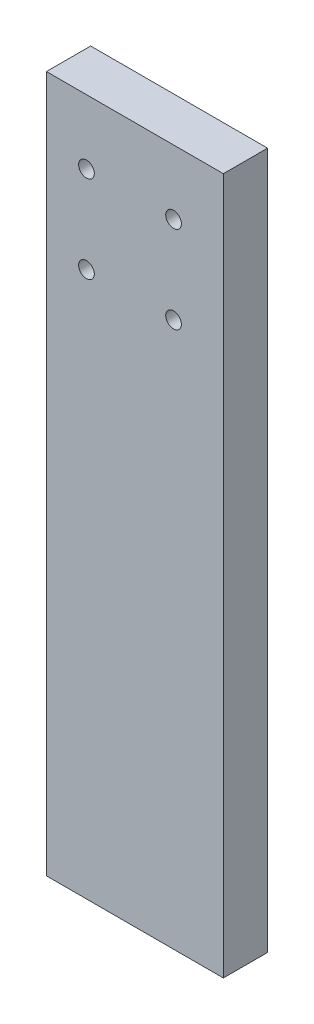
SolidWorks part; units mm, degrees
ref_plane "Alzado" through (0, 0, 0) normal (0, 0, 1) x (1, 0, 0)
ref_plane "Planta" through (0, 0, 0) normal (0, 1, 0) x (1, 0, 0)
ref_plane "Vista lateral" through (0, 0, 0) normal (1, 0, 0) x (0, 0, -1)
sketch "Croquis1" plane through (0, 0, 0) normal (0, 0, 1) x (1, 0, 0)
  line L1 (-24, 62) -> (26.8, 62)
  line L2 (-24, 62) -> (-24, -138)
  line L3 (-24, -138) -> (26.8, -138)
  line L4 (26.8, 62) -> (26.8, -138)
  circle A0 centre (-12.5, 18.5) radius 2.25 construction
  circle A1 centre (12.5, 18.5) radius 2.25 construction
  circle A2 centre (12.5, 43.5) radius 2.25 construction
  circle A3 centre (-12.5, 43.5) radius 2.25 construction
  circle A4 centre (-12.5, 18.5) radius 2.25
  circle A5 centre (12.5, 18.5) radius 2.25
  circle A6 centre (12.5, 43.5) radius 2.25
  circle A7 centre (-12.5, 43.5) radius 2.25
  dimension "D1" = 200
  dimension "D2" = 50.8
extrude "Saliente-Extruir1" add sketch "Croquis1" along normal blind 12.7 contours L4 L1 L2 L3 A7 A6 A5 A4
sketch "Croquis2" plane through (0, -138, 0) normal (0, -1, 0) x (1, 0, 0)
  line L0 (-24, 6.35) -> (26.8, 6.35) construction
  line L1 (-24, 12.7) -> (-24, 0) construction
  line L2 (26.8, 12.7) -> (26.8, 0) construction
  line L3 (1.4, 0) -> (1.4, 12.7) construction
  line L4 (-24, 12.7) -> (26.8, 12.7) construction
  circle A0 centre (-16.1, 6.35) radius 1.5
  circle A1 centre (18.9, 6.35) radius 1.5
  point P11 (1.4, 6.35)
  dimension "D1" = 3
  dimension "D2" = 3
  dimension "D3" = 17.5
  dimension "D4" = 17.5
extrude "Cortar-Extruir1" cut sketch "Croquis2" against normal blind 20
equation "\"D2@Croquis2\"=\"D1@Croquis2\""
equation "\"D4@Croquis2\"=\"D3@Croquis2\""
